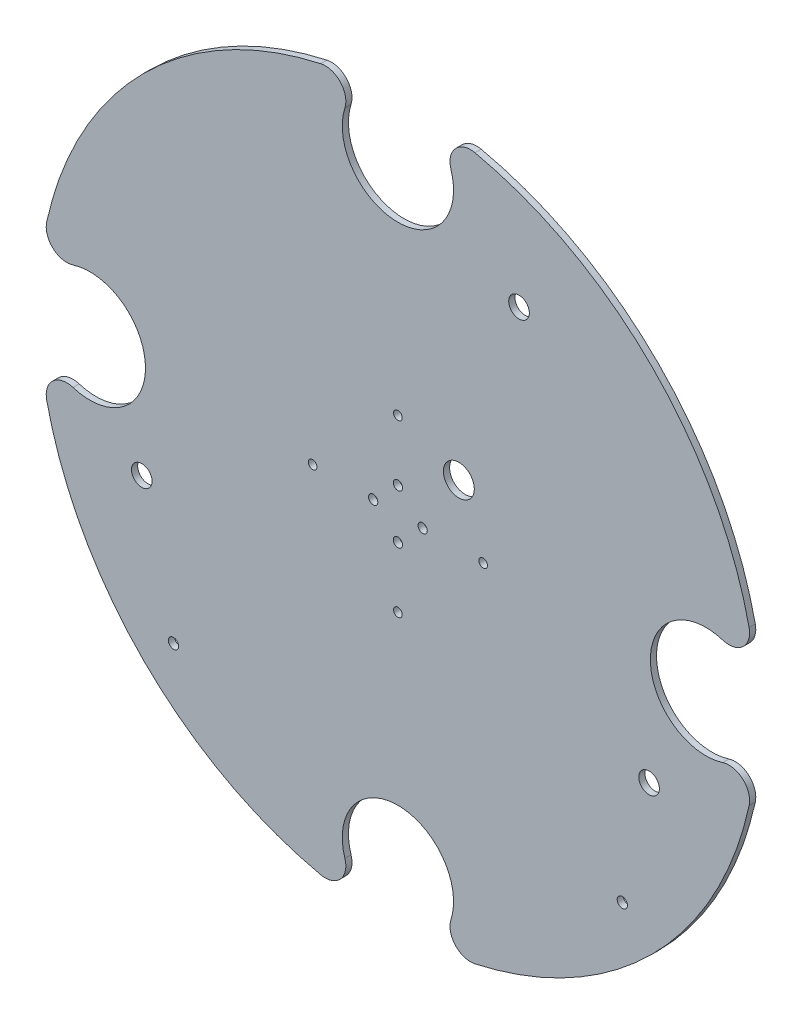
SolidWorks part; units mm, degrees
ref_plane "Front Plane" through (0, 0, 0) normal (0, 0, 1) x (1, 0, 0)
ref_plane "Top Plane" through (0, 0, 0) normal (0, 1, 0) x (1, 0, 0)
ref_plane "Right Plane" through (0, 0, 0) normal (1, 0, 0) x (0, 0, -1)
sketch "Sketch1" plane through (0, 0, 0) normal (0, 0, 1) x (1, 0, 0)
  line L0 (-174.5, 0) -> (174.5, 0) construction
  line L1 (0, 0) -> (110.6622, -110.6622) construction
  arc A4 (-170.4413, -37.4166) -> (-123.3901, -123.3901) centre (0, 0) ccw
  arc A5 (-157.6539, -25.7393) -> (-157.6539, 25.7393) centre (-149.5, 0) ccw
  arc A6 (-170.4413, 37.4166) -> (-157.6539, 25.7393) centre (-160.6739, 35.2724) ccw
  arc A7 (-170.4413, -37.4166) -> (-157.6539, -25.7393) centre (-160.6739, -35.2724) cw
  arc A8 (37.4166, 170.4413) -> (25.7393, 157.6539) centre (35.2724, 160.6739) ccw
  arc A9 (-25.7393, 157.6539) -> (25.7393, 157.6539) centre (0, 149.5) ccw
  arc A10 (-37.4166, 170.4413) -> (-25.7393, 157.6539) centre (-35.2724, 160.6739) cw
  arc A11 (170.4413, -37.4166) -> (157.6539, -25.7393) centre (160.6739, -35.2724) ccw
  arc A12 (157.6539, 25.7393) -> (157.6539, -25.7393) centre (149.5, 0) ccw
  arc A13 (170.4413, 37.4166) -> (157.6539, 25.7393) centre (160.6739, 35.2724) cw
  arc A14 (-37.4166, -170.4413) -> (-25.7393, -157.6539) centre (-35.2724, -160.6739) ccw
  arc A15 (25.7393, -157.6539) -> (-25.7393, -157.6539) centre (0, -149.5) ccw
  arc A16 (37.4166, -170.4413) -> (25.7393, -157.6539) centre (35.2724, -160.6739) cw
  arc A17 (-37.4166, 170.4413) -> (-125.4932, 121.2506) centre (0, 0) ccw
  arc A18 (170.4413, 37.4166) -> (121.2506, 125.4932) centre (0, 0) ccw
  arc A19 (37.4166, -170.4413) -> (170.4413, -37.4166) centre (0, 0) ccw
  circle A25 centre (12, 0) radius 2.25
  circle A26 centre (0, -12) radius 2.25
  circle A27 centre (-12, 0) radius 2.25
  circle A28 centre (0, 12) radius 2.25
  circle A29 centre (0, 0) radius 102.5 construction
  circle A30 centre (121.8734, -52.131) radius 5
  circle A31 centre (58.7754, 116.258) radius 5
  circle A32 centre (-124.2895, -46.0393) radius 5
  circle A33 centre (108.8944, -108.8944) radius 2.5
  circle A34 centre (-108.8944, -108.8944) radius 2.5
  arc A37 (-123.3901, -123.3901) -> (-37.4166, -170.4413) centre (0, 0) ccw
  arc A38 (-125.4932, 121.2506) -> (-170.4413, 37.4166) centre (0, 0) ccw
  arc A39 (121.2506, 125.4932) -> (37.4166, 170.4413) centre (0, 0) ccw
  circle A40 centre (41.37, 0) radius 2.1
  circle A41 centre (0, -41.37) radius 2.1
  circle A42 centre (-41.37, 0) radius 2.1
  circle A43 centre (0, 41.37) radius 2.1
  circle A44 centre (29.5728, 28.9297) radius 7.5
  circle A45 centre (-108.8944, 108.8944) radius 2.5 [skipped]
  circle A46 centre (108.8944, 108.8944) radius 2.5 [skipped]
  point P6 (0, 0)
  point P7 (0, 0)
  point P37 (0, 0)
  point P40 (5, 0)
  point P47 (0, 0)
  point P48 (9.75, 0)
  point P57 (0, 0)
  point P63 (0, 0)
  point P65 (0, 0)
  point P66 (0, 0)
  point P67 (0, 0)
  point P90 (0, 0)
  point P91 (0, 0)
  dimension "D1" = 25
  dimension "D3" = 4
  dimension "D2" = 27
  dimension "D4" = 4.2
  dimension "D5" = 41.37
  dimension "D7" = 4.5
  dimension "D9" = 4
  dimension "D10" = 10
  dimension "D11" = 10
  dimension "D12" = 10
  dimension "D14" = 5
  dimension "D19" = 15
  dimension "D16" = 174.5
  dimension "D8" = 12
  dimension "D13" = 45
  dimension "D15" = 154
  dimension "D20" = 41.37
  dimension "D18" = 4
  dimension "D6" = 4
extrude "Boss-Extrude2" add sketch "Sketch1" along normal blind 3
